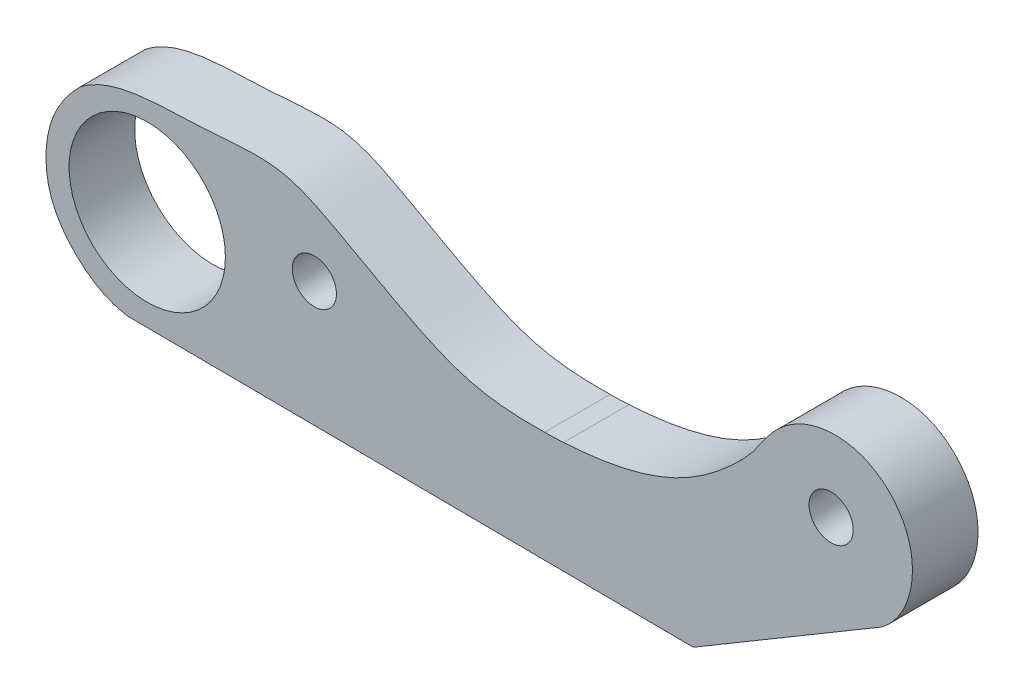
SolidWorks part; units mm, degrees
ref_plane "Piano frontale" through (0, 0, 0) normal (0, 0, 1) x (1, 0, 0)
ref_plane "Piano superiore" through (0, 0, 0) normal (0, 1, 0) x (1, 0, 0)
ref_plane "Piano destro" through (0, 0, 0) normal (1, 0, 0) x (0, 0, -1)
sketch "Schizzo2" plane through (0, 0, 0) normal (0, 0, 1) x (1, 0, 0)
  line L4 (-45.8065, 10.1385) -> (-29.7704, 19.6479)
  line L5 (-6.4285, 62.2183) -> (-12.7988, 61.6166)
  line L6 (-20.8222, 61.2865) -> (-45.448, 61.2865)
  line L7 (-89.3749, 10.4439) -> (-45.8065, 10.1385)
  line L8 (-45.8065, 10.1385) -> (-29.7704, 19.6479)
  line L9 (-6.4285, 62.2183) -> (-12.7988, 61.6166)
  line L10 (-20.8222, 61.2865) -> (-45.448, 61.2865)
  line L11 (-89.3749, 10.4439) -> (-45.8065, 10.1385)
  circle A0 centre (-74.9936, 19.9565) radius 1.7 construction
  circle A1 centre (-74.9936, 19.9565) radius 1.7
  circle A2 centre (-35.1891, 24.1136) radius 1.7 construction
  circle A3 centre (-35.1891, 24.1136) radius 1.7
  circle A4 centre (-87.8667, 18.1393) radius 6.02 construction
  circle A5 centre (-87.8667, 18.1393) radius 6.02
  ellipse E0 centre (-57.2563, 37.2981) end of major axis (-37.8063, 37.2981) minor radius 18.545 construction
  ellipse E1 centre (-57.2563, 37.2981) end of major axis (-37.8063, 37.2981) minor radius 18.545
  spline S0 degree 3 poles (-31.2793, 18.7531) (-29.098, 20.4037) (-27.9051, 25.4416) (-32.3004, 29.8584) (-36.6905, 29.9189) (-39.6149, 27.9424) (-41.0325, 25.5521) (-43.2846, 23.2416) (-48.1488, 19.5715) (-55.4824, 18.5532) (-63.1278, 18.896) (-68.3011, 21.4574) (-72.9856, 24.0866) (-76.3153, 25.8751) (-79.7395, 26.2367) (-83.2789, 25.795) (-88.2388, 25.8484) (-91.6892, 24.999) (-93.0837, 23.8512) knots 0 0 0 0 0.102244 0.160154 0.214293 0.256273 0.28915 0.319658 0.379342 0.518902 0.590345 0.669858 0.735081 0.798411 0.810363 0.866325 0.934004 1 1 1 1
  spline S3 degree 3 poles (-2218.9588, 2068.8042) (-79.5275, -43.7046) (-43.6365, -7.5711) (-19.5292, 31.9611) (-17.3272, 37.0506) (-14.922, 42.1161) (-12.0954, 46.687) (-8.8776, 49.9776) (-6.1277, 52.9833) (-2.8956, 55.0821) (-1.2594, 58.1768) (-11.0743, 81.1104) (-176.6376, -10.6875) (2229.9312, -1931.1386) knots -2.134089 -2.134089 -2.134089 -2.134089 0.205065 0.292072 0.382852 0.505732 0.597107 0.672729 0.755685 0.8164 0.883587 0.921519 2.094311 2.094311 2.094311 2.094311 only from (-29.7704, 19.6479) to (-6.4285, 62.2183)
  spline S4 degree 3 poles (1809.6411, -2321.2605) (-23.2093, 96.3948) (-9.901, 66.5969) (-14.4957, 59.5279) (-16.4659, 58.2209) (-19.0371, 59.2045) (-22.8328, 67.2183) (-31.9433, 35.8816) (-2956.0525, -557.6955) knots -2.12562 -2.12562 -2.12562 -2.12562 0.153142 0.247888 0.446916 0.809815 0.893165 2.948931 2.948931 2.948931 2.948931 only from (-12.7988, 61.6166) to (-20.8222, 61.2865)
  spline S5 degree 3 poles (-475.7337, 3025.3828) (137.2583, -122.0892) (19.0352, 79.4083) (-68.7052, 58.8464) (-73.7844, 57.362) (-77.6464, 56.2101) (-79.6123, 54.1168) (-79.7859, 51.8488) (-79.5708, 50.1209) (-79.8281, 48.2563) (-80.6297, 45.9722) (-81.574, 42.4408) (-82.9109, 38.1104) (-84.485, 33.6587) (-86.9307, 29.5959) (-89.5527, 26.432) (-93.1345, 24.132) (-95.2267, 21.2516) (-95.8242, 18.0471) (-95.4062, 15.1624) (-75.7495, -13.1735) (59.7591, 73.7569) (85.363, 3001.6392) knots -2.758541 -2.758541 -2.758541 -2.758541 0.193746 0.269881 0.346532 0.37765 0.40761 0.438995 0.45245 0.467917 0.503362 0.536032 0.594232 0.660243 0.698286 0.757936 0.800031 0.844688 0.876033 0.910905 0.942275 2.041439 2.041439 2.041439 2.041439 only from (-45.448, 61.2865) to (-89.3749, 10.4439)
  spline S6 degree 3 poles (-29.7704, 19.6479) (-26.177, 21.389) (-23.1961, 25.9479) (-19.5292, 31.9611) (-17.3272, 37.0506) (-14.922, 42.1161) (-12.0954, 46.687) (-8.8776, 49.9776) (-6.1277, 52.9833) (-2.8956, 55.0821) (-1.2594, 58.1768) (-2.6696, 61.4717) (-5.0083, 62.5113) (-6.4285, 62.2183) knots 0 0 0 0 0.205065 0.292072 0.382852 0.505732 0.597107 0.672729 0.755685 0.8164 0.883587 0.921519 1 1 1 1
  spline S7 degree 3 poles (-12.7988, 61.6166) (-13.4461, 61.691) (-13.6975, 60.756) (-14.4957, 59.5279) (-16.4659, 58.2209) (-19.0371, 59.2045) (-19.8762, 60.976) (-20.211, 61.2833) (-20.8222, 61.2865) knots 0 0 0 0 0.153142 0.247888 0.446916 0.809815 0.893165 1 1 1 1
  spline S8 degree 3 poles (-45.448, 61.2865) (-51.0279, 61.1688) (-58.9132, 61.1412) (-68.7052, 58.8464) (-73.7844, 57.362) (-77.6464, 56.2101) (-79.6123, 54.1168) (-79.7859, 51.8488) (-79.5708, 50.1209) (-79.8281, 48.2563) (-80.6297, 45.9722) (-81.574, 42.4408) (-82.9109, 38.1104) (-84.485, 33.6587) (-86.9307, 29.5959) (-89.5527, 26.432) (-93.1345, 24.132) (-95.2267, 21.2516) (-95.8242, 18.0471) (-95.4062, 15.1624) (-93.3152, 12.1482) (-91.0893, 10.6926) (-89.3749, 10.4439) knots 0 0 0 0 0.193746 0.269881 0.346532 0.37765 0.40761 0.438995 0.45245 0.467917 0.503362 0.536032 0.594232 0.660243 0.698286 0.757936 0.800031 0.844688 0.876033 0.910905 0.942275 1 1 1 1
  circle M8 centre (-74.9936, 19.9565) radius 1.7
  circle M9 centre (-35.1891, 24.1136) radius 1.7
  ellipse M11 centre (-57.2563, 37.2981) end of major axis (-37.8063, 37.2981) minor radius 18.545
  circle M14 centre (-87.8667, 18.1393) radius 6.02
  line M15 (-45.8065, 10.1385) -> (-29.7704, 19.6479)
  spline M20 degree 3 poles (-45.448, 61.2865) (-51.0279, 61.1688) (-58.9132, 61.1412) (-68.7052, 58.8464) (-73.7844, 57.362) (-77.6464, 56.2101) (-79.6123, 54.1168) (-79.7859, 51.8488) (-79.5708, 50.1209) (-79.8281, 48.2563) (-80.6297, 45.9722) (-81.574, 42.4408) (-82.9109, 38.1104) (-84.485, 33.6587) (-86.9307, 29.5959) (-89.5527, 26.432) (-93.1345, 24.132) (-95.2267, 21.2516) (-95.8242, 18.0471) (-95.4062, 15.1624) (-93.3152, 12.1482) (-91.0893, 10.6926) (-89.3749, 10.4439) knots 0 0 0 0 0.193746 0.269881 0.346532 0.37765 0.40761 0.438995 0.45245 0.467917 0.503362 0.536032 0.594232 0.660243 0.698286 0.757936 0.800031 0.844688 0.876033 0.910905 0.942275 1 1 1 1
  line M21 (-89.3749, 10.4439) -> (-45.8065, 10.1385)
  dimension "D1" = 0
extrude "Estrusione-Estrusione1" add sketch "Schizzo2" along normal blind 5.05 contours S0 M15 M11 M20 M21 M8 M14 M9
